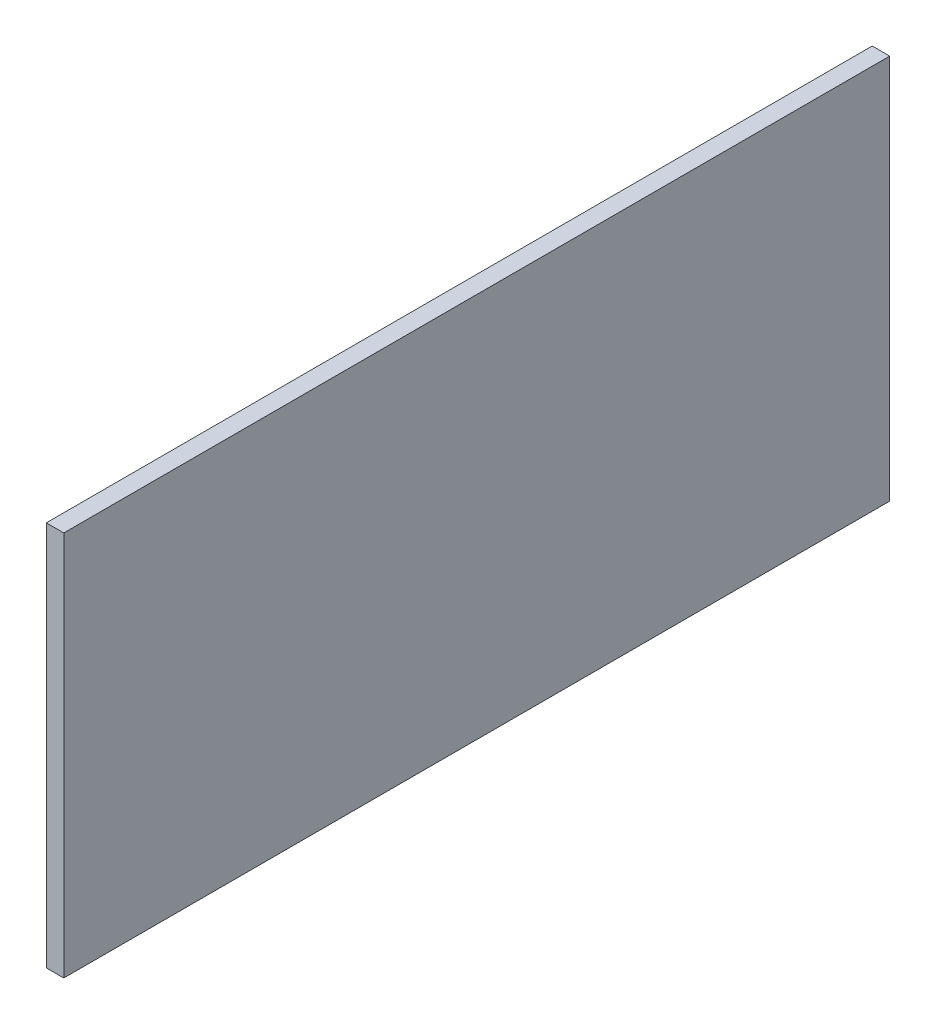
SolidWorks part; units mm, degrees
ref_plane "Front Plane" through (0, 0, 0) normal (0, 0, 1) x (1, 0, 0)
ref_plane "Top Plane" through (0, 0, 0) normal (0, 1, 0) x (1, 0, 0)
ref_plane "Right Plane" through (0, 0, 0) normal (1, 0, 0) x (0, 0, -1)
sketch "Sketch1" plane through (0, 0, 0) normal (1, 0, 0) x (0, 0, -1)
  line L1 (0, 0) -> (150, 0)
  line L2 (0, 0) -> (0, 70)
  line L3 (0, 70) -> (150, 70)
  line L4 (150, 0) -> (150, 70)
  dimension "D1" = 70
  dimension "D2" = 150
extrude "Boss-Extrude1" add sketch "Sketch1" along normal blind 3.175
